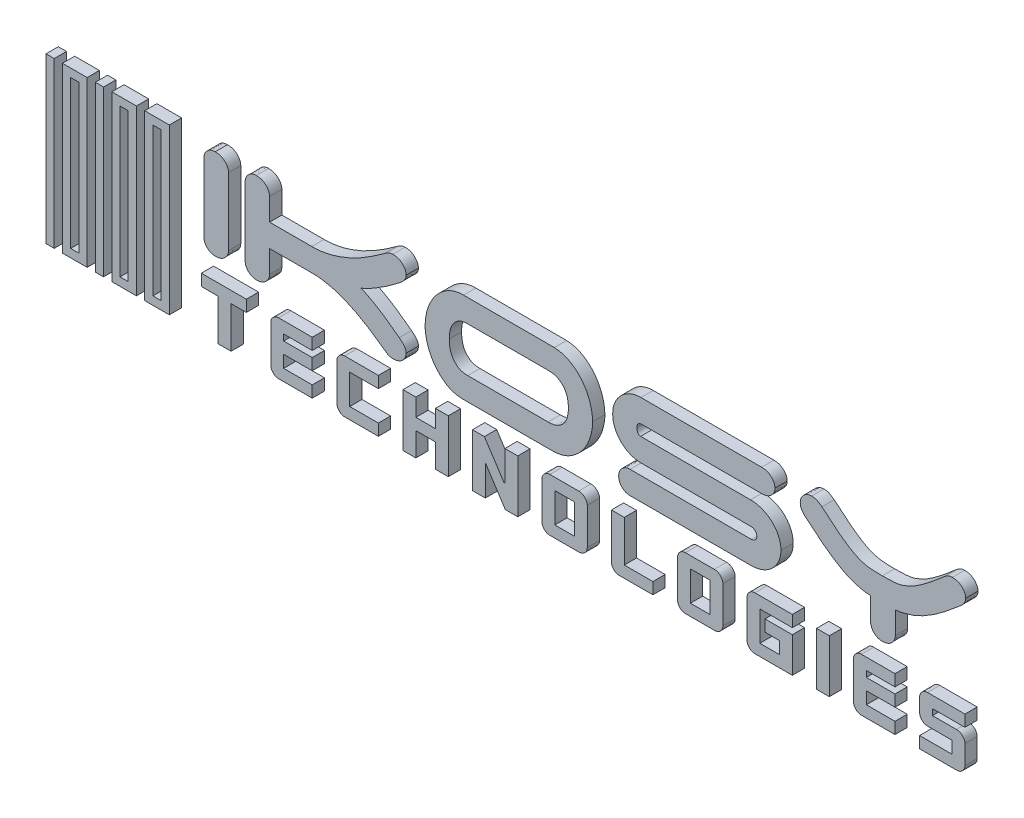
SolidWorks part; units mm, degrees
other "Text Extrude Y"
other "Text Extrude S"
other "Text Extrude O"
other "Text Extrude K"
other "Text Extrude I"
other "Symbol Extrude 3-1"
other "Symbol Extrude 2-0"
other "Symbol Extrude 1-1" parameters "D1"=6.2983, "D2"=2.0167, "D3"=11.6967, "D4"=11.6967, "D5"=1.4517, "D6"=1.4517, "D7"=14.1973, "D8"=14.1973, "D9"=30.15, "D10"=33.5, "D11"=33.5, "D12"=33.5, "D13"=30.15
ref_plane "Front Plane" through (0, 0, 0) normal (0, 0, 1) x (1, 0, 0)
ref_plane "Top Plane" through (0, 0, 0) normal (0, 1, 0) x (1, 0, 0)
ref_plane "Right Plane" through (0, 0, 0) normal (1, 0, 0) x (0, 0, -1)
sketch "Insertion Point Sketch" plane through (0, 0, 0) normal (0, 0, 1) x (1, 0, 0)
  line L0 (-3.25, -3.25) -> (-3.25, 0) construction
  line L1 (-3.25, -3.25) -> (0, -3.25) construction
  dimension "D1" = 3.25
  dimension "D2" = 3.25
ref_plane "3D Printing Base Plane" through (0, 0, -4) normal (0, 0, 1) x (1, 0, 0)
sketch "3D Printing Origin Sketch" plane through (0, 0, -4) normal (0, 0, 1) x (1, 0, 0)
  point P0 (-24.5, -6.5)
  dimension "D1" = 21.25
  dimension "D2" = 3.25
sketch "Symbol Sketch" plane through (0, 0, 0) normal (0, 0, 1) x (1, 0, 0)
  line L1 (-3.25, 30.25) -> (-1.575, 30.25)
  line L2 (-3.25, 30.25) -> (-3.25, -3.25)
  line L3 (-3.25, -3.25) -> (-1.575, -3.25)
  line L4 (-1.575, 30.25) -> (-1.575, -3.25)
  line L5 (1.775, 28.575) -> (3.45, 28.575)
  line L6 (1.775, 28.575) -> (1.775, -1.575)
  line L7 (1.775, -1.575) -> (3.45, -1.575)
  line L8 (3.45, 28.575) -> (3.45, -1.575)
  line L9 (0.1, 30.25) -> (5.125, 30.25)
  line L10 (0.1, 30.25) -> (0.1, -3.25)
  line L11 (0.1, -3.25) -> (5.125, -3.25)
  line L12 (5.125, 30.25) -> (5.125, -3.25)
  line L13 (6.8, 30.25) -> (8.475, 30.25)
  line L14 (6.8, 30.25) -> (6.8, -3.25)
  line L15 (6.8, -3.25) -> (8.475, -3.25)
  line L16 (8.475, 30.25) -> (8.475, -3.25)
  line L17 (10.15, 30.25) -> (15.175, 30.25)
  line L18 (10.15, 30.25) -> (10.15, -3.25)
  line L19 (10.15, -3.25) -> (15.175, -3.25)
  line L20 (15.175, 30.25) -> (15.175, -3.25)
  line L21 (11.825, 28.575) -> (13.5, 28.575)
  line L22 (11.825, 28.575) -> (11.825, -1.575)
  line L23 (11.825, -1.575) -> (13.5, -1.575)
  line L24 (13.5, 28.575) -> (13.5, -1.575)
  line L25 (16.85, 30.25) -> (21.875, 30.25)
  line L26 (16.85, 30.25) -> (16.85, -3.25)
  line L27 (16.85, -3.25) -> (21.875, -3.25)
  line L28 (21.875, 30.25) -> (21.875, -3.25)
  line L29 (18.525, 28.575) -> (20.2, 28.575)
  line L30 (18.525, 28.575) -> (18.525, -1.575)
  line L31 (18.525, -1.575) -> (20.2, -1.575)
  line L32 (20.2, 28.575) -> (20.2, -1.575)
  dimension "D1" = 1.675
  dimension "D2" = 1.675
  dimension "D3" = 1.675
  dimension "D4" = 1.675
  dimension "D5" = 1.675
  dimension "D6" = 1.675
  dimension "D7" = 1.675
  dimension "D8" = 33.5
  dimension "D9" = 1.675
  dimension "D10" = 1.675
  dimension "D11" = 1.675
  dimension "D12" = 1.675
  dimension "D13" = 1.675
extrude "Symbol Extrude" add sketch "Symbol Sketch" along normal blind 2.5
sketch "Text Sketch" plane through (0, 0, 0) normal (0, 0, 1) x (1, 0, 0)
  line L0 (21.875, 30.25) -> (184.25, 30.25) construction
  line L1 (184.25, 30.25) -> (184.25, -3.25) construction
  text T0 "ikosy" font "Space Age" height 18.425
  text T1 "TECHNOLOGIES" font "Alien Encounters Solid" height 10.75
  dimension "D3" = 1.1
  dimension "D2" = 12.075
  dimension "D1" = 30.125
  dimension "D4" = 187.5
extrude "Text Extrude" add sketch "Text Sketch" along normal blind 2.5 separate body
equation "\"Logo Height\"= \"Total Height\" - 2 * \"Border\""
equation "\"Total Height\"= 40mm"
equation "\"Border\"= 3.25mm"
equation "\"Symbol Width\"= \"Logo Height\" * 0.75"
equation "\"Line Width\"= \"Symbol Width\" / 15"
equation "\"D2@Symbol Sketch\" = \"Line Width\""
equation "\"D1@Symbol Sketch\" = \"Line Width\""
equation "\"D3@Symbol Sketch\" = \"Line Width\""
equation "\"D4@Symbol Sketch\" = \"Line Width\""
equation "\"D5@Symbol Sketch\" = \"Line Width\""
equation "\"D6@Symbol Sketch\" = \"Line Width\""
equation "\"D7@Symbol Sketch\" = \"Line Width\""
equation "\"D8@Symbol Sketch\" = \"Logo Height\""
equation "\"D9@Symbol Sketch\" = \"Line Width\""
equation "\"D10@Symbol Sketch\" = \"Line Width\""
equation "\"D11@Symbol Sketch\" = \"Line Width\""
equation "\"D12@Symbol Sketch\" = \"Line Width\""
equation "\"D13@Symbol Sketch\" = \"Line Width\""
equation "\"Ikosy X Position\"= \"Symbol Width\" + 5mm"
equation "\"Ikosy Y Position\"= ( 1 - 0.55 ) * \"Logo Height\" - 3"
equation "\"D1@Insertion Point Sketch\" = \"Border\""
equation "\"D2@Insertion Point Sketch\" = \"Border\""
equation "\"D2@Text Sketch\"=\"Ikosy Y Position\""
equation "\"D1@Text Sketch\"=\"Ikosy X Position\""
